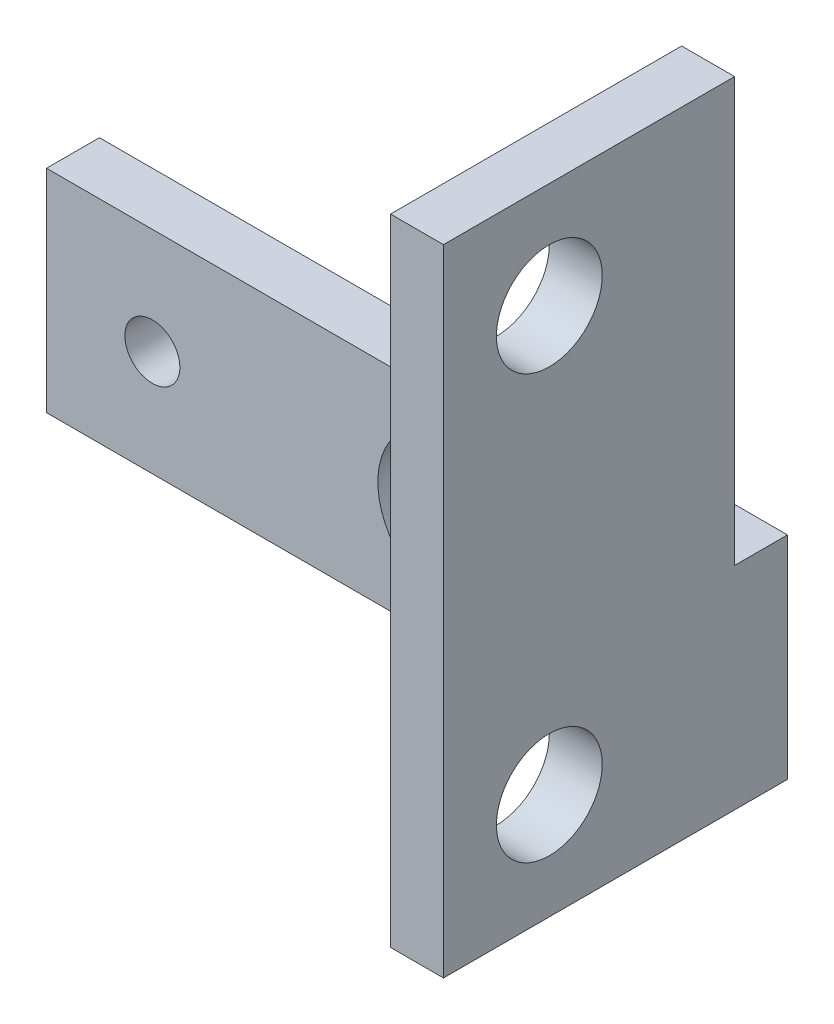
SolidWorks part; units mm, degrees
ref_plane "Front Plane" through (0, 0, 0) normal (0, 0, 1) x (1, 0, 0)
ref_plane "Top Plane" through (0, 0, 0) normal (0, 1, 0) x (1, 0, 0)
ref_plane "Right Plane" through (0, 0, 0) normal (1, 0, 0) x (0, 0, -1)
sketch "Sketch1" plane through (0, 0, 0) normal (0, 0, 1) x (1, 0, 0)
  line L0 (0, 0) -> (82.55, 0)
  line L1 (82.55, 0) -> (82.55, 25.4)
  line L2 (82.55, 25.4) -> (0, 25.4)
  line L3 (0, 25.4) -> (0, 0)
  dimension "D1" = 25.4
  dimension "D2" = 82.55
extrude "Boss-Extrude1" add sketch "Sketch1" along normal blind 6.35
sketch "Sketch2" plane through (0, 0, 6.35) normal (0, 0, 1) x (1, 0, 0)
  line L0 (82.55, 25.4) -> (76.2, 25.4)
  line L1 (82.55, 25.4) -> (0, 25.4) construction
  line L2 (76.2, 25.4) -> (76.2, 0)
  line L3 (0, 0) -> (82.55, 0) construction
  line L4 (76.2, 0) -> (82.55, 0)
  line L5 (82.55, 0) -> (82.55, 25.4) construction
  line L6 (82.55, 0) -> (82.55, 25.4)
  dimension "D1" = 6.35
extrude "Boss-Extrude2" add sketch "Sketch2" along normal blind 34.925
sketch "Sketch4" plane through (82.55, 0, 0) normal (1, 0, 0) x (0, 0, -1)
  line L0 (-41.275, 0) -> (-41.275, 25.4) construction
  line L3 (-41.275, 0) -> (0, 0) construction
  circle A0 centre (-28.575, 12.7) radius 6.35
  dimension "D1" = 12.7
  dimension "D2" = 12.7
  dimension "D3" = 12.7
extrude "Cut-Extrude1" cut sketch "Sketch4" against normal through all
sketch "Sketch5" plane through (0, 0, 6.35) normal (0, 0, 1) x (1, 0, 0)
  line L1 (0, 0) -> (76.2, 0) construction
  line L2 (0, 25.4) -> (0, 0) construction
  circle A0 centre (12.7, 12.7) radius 3.302
  circle A1 centre (48.895, 12.7) radius 9.144
  dimension "D3" = 6.604
  dimension "D4" = 18.288
  dimension "D1" = 12.7
  dimension "D2" = 12.7
  dimension "D5" = 12.7
  dimension "D6" = 36.195
extrude "Cut-Extrude2" cut sketch "Sketch5" against normal blind 38.1
sketch "Sketch6" plane through (0, 25.4, 0) normal (0, 1, 0) x (1, 0, 0)
  line L0 (76.2, -6.35) -> (82.55, -6.35)
  line L1 (82.55, -41.275) -> (82.55, 0) construction
  line L2 (82.55, -6.35) -> (82.55, -41.275)
  line L3 (82.55, -41.275) -> (76.2, -41.275)
  line L4 (76.2, -41.275) -> (76.2, -6.35)
extrude "Boss-Extrude3" add sketch "Sketch6" along normal blind 50.8
sketch "Sketch7" plane through (82.55, 0, 0) normal (1, 0, 0) x (0, 0, -1)
  line L0 (-41.275, 0) -> (-41.275, 76.2) construction
  line L1 (-41.275, 76.2) -> (-6.35, 76.2) construction
  circle A0 centre (-28.575, 63.5) radius 6.35
  dimension "D1" = 12.7
  dimension "D2" = 12.7
  dimension "D3" = 12.7
extrude "Cut-Extrude3" cut sketch "Sketch7" against normal through all
